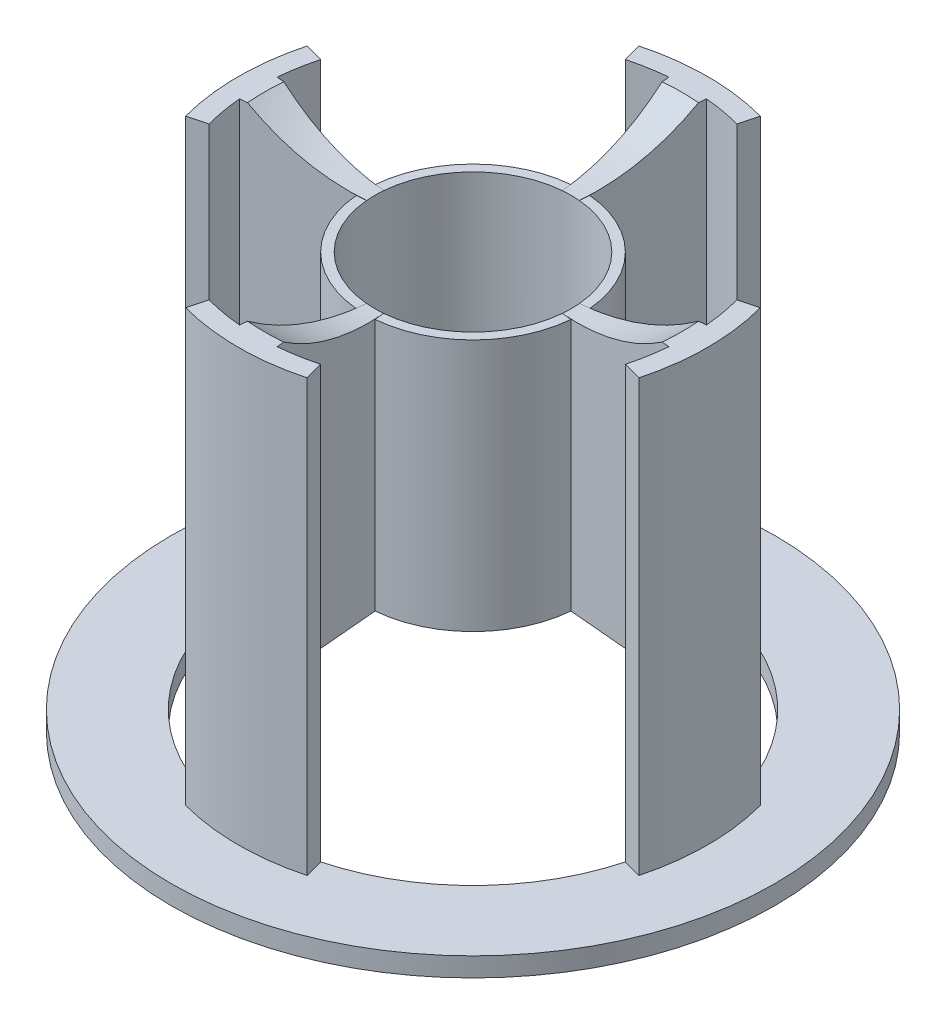
SolidWorks part; units mm, degrees
ref_plane "Front Plane" through (0, 0, 0) normal (0, 0, 1) x (1, 0, 0)
ref_plane "Top Plane" through (0, 0, 0) normal (0, 1, 0) x (1, 0, 0)
ref_plane "Right Plane" through (0, 0, 0) normal (1, 0, 0) x (0, 0, -1)
sketch "Esboço1" plane through (0, 0, 0) normal (0, 1, 0) x (1, 0, 0)
  circle A0 centre (0, 0) radius 31.5
  circle A1 centre (0, 0) radius 22.5
  dimension "D1" = 63
  dimension "D2" = 45
extrude "Ressalto-extrusão1" add sketch "Esboço1" along normal blind 2
sketch "Esboço3" plane through (0, 2, 0) normal (0, 1, 0) x (1, 0, 0)
  line L0 (-5.8234, -21.7333) -> (-6.3411, -23.6652)
  line L1 (5.8234, -21.7333) -> (6.3411, -23.6652)
  line L2 (-5.8234, -21.7333) -> (0, 0) construction
  line L3 (5.8234, -21.7333) -> (0, 0) construction
  line L4 (-21.7333, -5.8234) -> (-23.6652, -6.3411)
  line L5 (-21.7333, 5.8234) -> (-23.6652, 6.3411)
  line L6 (-21.7333, -5.8234) -> (0, 0) construction
  line L7 (-21.7333, 5.8234) -> (0, 0) construction
  line L8 (-5.8234, 21.7333) -> (-6.3411, 23.6652)
  line L9 (5.8234, 21.7333) -> (6.3411, 23.6652)
  line L10 (-5.8234, 21.7333) -> (0, 0) construction
  line L11 (5.8234, 21.7333) -> (0, 0) construction
  line L12 (21.7333, 5.8234) -> (23.6652, 6.3411)
  line L13 (21.7333, -5.8234) -> (23.6652, -6.3411)
  line L14 (21.7333, 5.8234) -> (0, 0) construction
  line L15 (21.7333, -5.8234) -> (0, 0) construction
  arc A0 (-6.3411, -23.6652) -> (6.3411, -23.6652) centre (0, 0) ccw
  arc A1 (-5.8234, -21.7333) -> (5.8234, -21.7333) centre (0, 0) ccw
  circle A2 centre (0, 0) radius 22.5 construction
  arc A3 (-23.6652, 6.3411) -> (-23.6652, -6.3411) centre (0, 0) ccw
  arc A4 (-21.7333, 5.8234) -> (-21.7333, -5.8234) centre (0, 0) ccw
  arc A5 (6.3411, 23.6652) -> (-6.3411, 23.6652) centre (0, 0) ccw
  arc A6 (5.8234, 21.7333) -> (-5.8234, 21.7333) centre (0, 0) ccw
  arc A7 (23.6652, -6.3411) -> (23.6652, 6.3411) centre (0, 0) ccw
  arc A8 (21.7333, -5.8234) -> (21.7333, 5.8234) centre (0, 0) ccw
  dimension "D1" = 49
  dimension "D2" = 30
  dimension "D3" = 4
extrude "Ressalto-extrusão2" add sketch "Esboço3" along normal blind 45
sketch "Esboço4" plane through (0, 0, 0) normal (0, 0, 1) x (1, 0, 0)
  line L0 (-24.5, 47) -> (-21.7333, 47)
  line L1 (-10.25, 43.3748) -> (-10.25, 17)
  line L3 (-24.5, 17) -> (-24.5, 47)
  line L4 (0, 0) -> (0, 47) construction
  line L5 (-31.5, 0) -> (31.5, 0) construction
  line L6 (6.3411, 47) -> (-6.3411, 47) construction
  line L7 (-10.25, 17) -> (-24.5, 17)
  line L8 (10.25, 17) -> (24.5, 17)
  line L9 (24.5, 47) -> (21.7333, 47)
  line L10 (24.5, 17) -> (24.5, 47)
  line L11 (10.25, 43.3748) -> (10.25, 17)
  arc A0 (-21.7333, 47) -> (-10.25, 43.3748) centre (-10.25, 63.3748) ccw
  arc A2 (21.7333, 47) -> (10.25, 43.3748) centre (10.25, 63.3748) cw
  dimension "D1" = 10.25
  dimension "D3" = 20
  dimension "D2" = 30
revolve "Revolução1" add sketch "Esboço4" angle 10 mid plane about L4
sketch3d "3DSketch1"
  line L0 (0, 0, 0) -> (0, 61.1667, 0) construction
pattern_circular "PadrãoCircular1" count 2 every 90 about axis through (0, 0, 0) along (0, 1, 0) of "Revolução1"
sketch "Esboço5" plane through (0, 17, 0) normal (0, -1, 0) x (1, 0, 0)
  circle A0 centre (0, 0) radius 11.25
  circle A1 centre (0, 0) radius 10.25
  arc A2 (0.8933, 10.211) -> (-0.8933, 10.211) centre (0, 0) ccw construction
  dimension "D1" = 1
extrude "Ressalto-extrusão3" add sketch "Esboço5" against normal up to vertex (26.3748 mm away)
